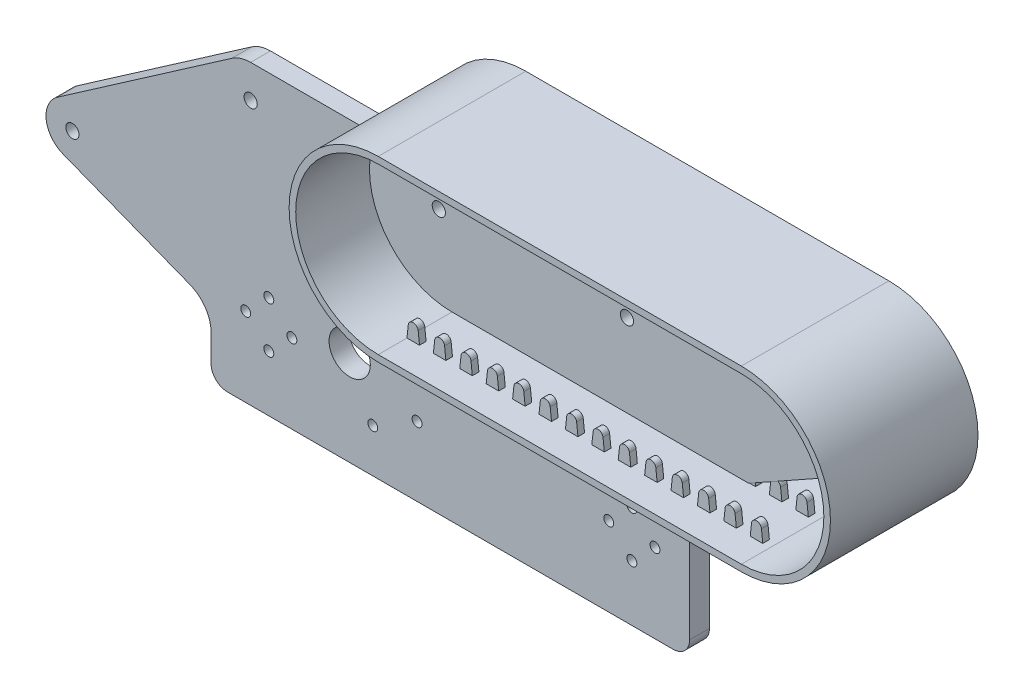
SolidWorks part; units mm, degrees
material "PE(聚乙烯)"
ref_plane "前视" through (0, 0, 0) normal (0, 0, 1) x (1, 0, 0)
ref_plane "上视" through (0, 0, 0) normal (0, 1, 0) x (1, 0, 0)
ref_plane "右视" through (0, 0, 0) normal (1, 0, 0) x (0, 0, -1)
sketch "草图1" plane through (0, 0, 0) normal (0, 0, 1) x (1, 0, 0)
  line L0 (0, 5) -> (0, 13.1711)
  line L1 (-6.3606, 22.4853) -> (-44.9115, 37.5486)
  line L2 (-46.5577, 51.5747) -> (6.3029, 88.2184)
  line L3 (12, 90) -> (187, 90)
  line L4 (191.8887, 71.2764) -> (150.1113, 47.8644)
  line L5 (145, 39.1408) -> (145, 5)
  line L6 (140, 0) -> (5, 0)
  line L7 (183, 80) -> (187, 80) construction
  line L8 (183, 82) -> (187, 82)
  line L9 (183, 78) -> (187, 78)
  line L10 (42, 28.75) -> (42, -5.2333) construction
  line L11 (42, 28.75) -> (80.8482, 28.75) construction
  line L12 (49, 28.75) -> (49, 13.25) construction
  line L13 (62.4234, 21) -> (49, 28.75) construction
  line L14 (49, 28.75) -> (62.4234, 36.5) construction
  arc A0 (-44.9115, 37.5486) -> (-46.5577, 51.5747) centre (-42, 45) cw
  arc A1 (187, 90) -> (191.8887, 71.2764) centre (187, 80) cw
  circle A2 centre (-42, 45) radius 2
  circle A3 centre (12, 80) radius 2
  circle A4 centre (69, 80) radius 2
  circle A5 centre (126, 80) radius 2
  arc A6 (183, 82) -> (183, 78) centre (183, 80) ccw
  arc A7 (187, 78) -> (187, 82) centre (187, 80) ccw
  arc A8 (12, 90) -> (6.3029, 88.2184) centre (12, 80) ccw
  arc A9 (145, 39.1408) -> (150.1113, 47.8644) centre (155, 39.1408) cw
  arc A10 (0, 13.1711) -> (-6.3606, 22.4853) centre (-10, 13.1711) ccw
  arc A11 (145, 5) -> (140, 0) centre (140, 5) cw
  arc A12 (5, 0) -> (0, 5) centre (5, 5) cw
  circle A13 centre (42, 28.75) radius 6.25
  circle A14 centre (42, 21.75) radius 18.5 construction
  circle A15 centre (49, 28.75) radius 18.5 construction
  circle A16 centre (49, 44.25) radius 1.5
  circle A17 centre (49, 28.75) radius 15.5 construction
  circle A18 centre (49, 13.25) radius 1.5
  circle A19 centre (62.4234, 21) radius 1.5
  circle A20 centre (62.4234, 36.5) radius 1.5
  point P20 (185, 80)
  point P28 (145, 45)
  point P31 (0, 20)
  point P34 (145, 0)
  point P37 (0, 0)
  dimension "D4" = 10
  dimension "D6" = 8
  dimension "D7" = 4
  dimension "D8" = 42
  dimension "D9" = 45
  dimension "D10" = 12
  dimension "D11" = 10
  dimension "D13" = 57
  dimension "D14" = 8
  dimension "D15" = 2
  dimension "D16" = 59
  dimension "D17" = 10
  dimension "D18" = 5
  dimension "D19" = 12.5
  dimension "D20" = 55
  dimension "D21" = 42
  dimension "D22" = 37
  dimension "D24" = 37
  dimension "D26" = 3
  dimension "D27" = 31
  dimension "D28" = 60
  dimension "D1" = 90
  dimension "D2" = 145
  dimension "D3" = 45
  dimension "D5" = 20
  dimension "D12" = 57
  dimension "D23" = 7
  dimension "D25" = 7
  dimension "D29" = 60
extrude "凸台-拉伸1" add sketch "草图1" along normal blind 6
sketch "草图2" plane through (0, 0, 0) normal (0, 0, -1) x (-1, 0, 0)
  line L0 (-17.5, 24) -> (-127.5, 24) construction
  line L1 (-5, 0) -> (-140, 0) construction
  line L2 (0, 13.1711) -> (0, 5) construction
  line L3 (-145, 5) -> (-145, 39.1408) construction
  circle A0 centre (-17.5, 24) radius 4 construction
  circle A1 centre (-127.5, 24) radius 4 construction
  circle A2 centre (-17.5, 24) radius 7 construction
  circle A3 centre (-127.5, 24) radius 7 construction
  circle A4 centre (-17.5, 17) radius 1.5
  circle A5 centre (-24.5, 24) radius 1.5
  circle A6 centre (-17.5, 31) radius 1.5
  circle A7 centre (-10.5, 24) radius 1.5
  circle A8 centre (-127.5, 17) radius 1.5
  circle A9 centre (-134.5, 24) radius 1.5
  circle A10 centre (-127.5, 31) radius 1.5
  circle A11 centre (-120.5, 24) radius 1.5
  dimension "D1" = 8
  dimension "D3" = 17.5
  dimension "D4" = 17.5
  dimension "D5" = 14
  dimension "D6" = 14
  dimension "D7" = 3
  dimension "D2" = 24
extrude "切除-拉伸1" cut sketch "草图2" against normal blind 10
sketch "草图3" plane through (0, 0, 6) normal (0, 0, 1) x (1, 0, 0)
  line L0 (73, 54) -> (183, 54)
  line L2 (73, 106) -> (183, 106)
  arc A2 (183, 54) -> (183, 106) centre (183, 80) ccw
  circle A3 centre (203, 80) radius 26 construction
  arc A10 (73, 106) -> (73, 54) centre (73, 80) ccw
  dimension "D1" = 130
  dimension "D2" = 52
  dimension "D4" = 110
  dimension "D6" = 52
ref_plane "基准面1" through (73, 54, 6) normal (1, 0, 0) x (0, 0, -1)
sketch "草图5" plane through (73, 54, 6) normal (1, 0, 0) x (0, 0, -1)
  line L0 (0, 52) -> (0, 0) construction
  line L1 (22.35, -1) -> (-22.35, -1)
  line L2 (22.35, -1) -> (22.35, 1)
  line L3 (22.35, 1) -> (-22.35, 1)
  line L4 (-22.35, -1) -> (-22.35, 1)
  line L5 (22.35, -1) -> (-22.35, 1) construction
  line L6 (22.35, 1) -> (-22.35, -1) construction
  line L7 (0, 52) -> (0, 0) construction
  point P0 (0, 0)
  dimension "D1" = 2
  dimension "D2" = 44.7
sweep "扫描1" add profiles "草图5" path "草图3"
sketch "草图6" plane through (0, 55, 0) normal (0, 1, 0) x (1, 0, 0)
  line L0 (73, -28.35) -> (183, -28.35) construction
  line L1 (73, -3.85) -> (76.8, -3.85)
  line L2 (73, -3.85) -> (73, -5.85)
  line L3 (73, -5.85) -> (76.8, -5.85)
  line L4 (76.8, -3.85) -> (76.8, -5.85)
  line L5 (73, -17.65) -> (76.8, -17.65)
  line L6 (73, -17.65) -> (73, -19.65)
  line L7 (73, -19.65) -> (76.8, -19.65)
  line L8 (76.8, -17.65) -> (76.8, -19.65)
  line L10 (73, -28.35) -> (73, 16.35) construction
  dimension "D1" = 2
  dimension "D2" = 2
  dimension "D3" = 3.8
  dimension "D4" = 3.8
  dimension "D5" = 11.8
  dimension "D6" = 8.7
extrude "凸台-拉伸2" add sketch "草图6" along normal blind 10
sketch "草图7" plane through (0, 0, 19.65) normal (0, 0, 1) x (1, 0, 0)
  line L0 (74.9, 65) -> (74.9, 55) construction
  line L1 (73, 65) -> (76.8, 65) construction
  line L2 (73, 55) -> (76.8, 55) construction
  line L3 (73.4, 58.6552) -> (73, 55)
  line L4 (73, 65) -> (73, 55) construction
  line L5 (183, 55) -> (73, 55) construction
  line L6 (76.4, 58.6552) -> (76.8, 55)
  line L7 (76.8, 65) -> (76.8, 55) construction
  line L8 (73, 55) -> (73, 65)
  line L9 (73, 65) -> (76.8, 65)
  line L10 (76.8, 65) -> (76.8, 55)
  arc A0 (73.4, 58.6552) -> (76.4, 58.6552) centre (74.9, 58.491) cw
  dimension "D1" = 5
  dimension "D2" = 3
extrude "切除-拉伸2" cut sketch "草图7" against normal blind 19
ref_plane "基准面2" through (0, 80, 0) normal (0, 1, 0) x (1, 0, 0)
mirror "镜向1" about plane through (0, 80, 0) normal (0, 1, 0) of "切除-拉伸2", "凸台-拉伸2"
pattern_linear "阵列(线性)2" count 14 spacing 8 along (1, 0, 0) of "凸台-拉伸2", "镜向1", "切除-拉伸2"
ref_plane "基准面3" through (73.4, 58.6552, 19.65) normal (0.1088, 0.9941, 0) x (0.9941, -0.1088, 0)
ref_plane "基准面4" through (0, 0, 11.75) normal (0, 0, 1) x (1, 0, 0)
ref_plane "基准面5" through (183, 0, 0) normal (1, 0, 0) x (0, 0, -1)
ref_plane "基准面6" through (53, 0, 0) normal (1, 0, 0) x (0, 0, -1)
